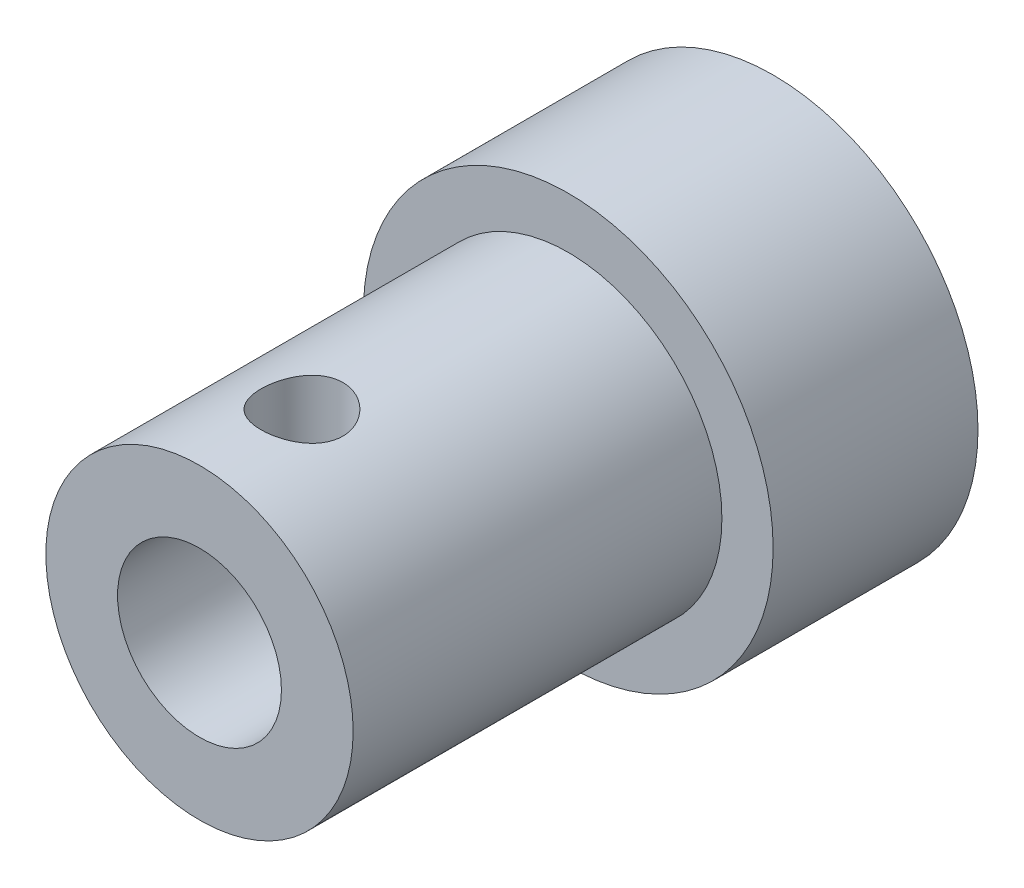
SolidWorks part; units mm, degrees
material "1060 Alloy"
ref_plane "Front Plane" through (0, 0, 0) normal (0, 0, 1) x (1, 0, 0)
ref_plane "Top Plane" through (0, 0, 0) normal (0, 1, 0) x (1, 0, 0)
ref_plane "Right Plane" through (0, 0, 0) normal (1, 0, 0) x (0, 0, -1)
sketch "Sketch1" plane through (0, 0, 0) normal (0, 0, 1) x (1, 0, 0)
  circle A0 centre (0, 0) radius 4
  circle A1 centre (0, 0) radius 7.5
  dimension "D1" = 8
  dimension "D2" = 15
extrude "Boss-Extrude1" add sketch "Sketch1" against normal blind 5 contours A0 | A1 A0
ref_plane "Plane1" through (0, 7.5, 0) normal (0, 1, 0) x (1, 0, 0)
sketch "Sketch3" plane through (0, 0, -5) normal (0, 0, -1) x (-1, 0, 0)
  line L0 (0, 0) -> (0, 7) construction
  line L1 (0, 0) -> (7, 0) construction
  circle A0 centre (0, 0) radius 10
  circle A1 centre (0, 7) radius 1.5
  circle A2 centre (7, 0) radius 1.5
  circle A3 centre (0, -7) radius 1.5
  circle A4 centre (-7, 0) radius 1.5
  dimension "D1" = 20
  dimension "D2" = 3
  dimension "D3" = 7
  dimension "D5" = 90
  dimension "D6" = 7
  dimension "D4" = 4
extrude "Boss-Extrude3" add sketch "Sketch3" along normal blind 8
sketch "Sketch4" plane through (0, 0, 0) normal (0, 0, 1) x (1, 0, 0)
  circle A0 centre (0, 0) radius 4
  circle A1 centre (0, 0) radius 7.5
  circle A2 centre (0, 0) radius 7.5
  dimension "D2" = 8
  dimension "D1" = 0
extrude "Boss-Extrude4" add sketch "Sketch4" along normal blind 15
sketch "Sketch2" plane through (0, 7.5, 0) normal (0, 1, 0) x (1, 0, 0)
  circle A0 centre (0, -10) radius 2
  dimension "D2" = 4
  dimension "D1" = 10
extrude "Cut-Extrude1" cut sketch "Sketch2" against normal blind 7
sketch "Sketch6" plane through (0, 0, 15) normal (0, 0, 1) x (1, 0, 0)
  circle A0 centre (0, 0) radius 4 construction
  circle A1 centre (0, 0) radius 4
extrude "Cut-Extrude2" cut sketch "Sketch6" against normal through all
sketch "Sketch7" plane through (0, 0, -5) normal (0, 0, 1) x (1, 0, 0)
  circle A0 centre (0, 0) radius 10 construction
  circle A1 centre (0, 0) radius 10
  circle A2 centre (0, 0) radius 4 construction
  circle A3 centre (0, 0) radius 4
extrude "Boss-Extrude5" add sketch "Sketch7" along normal blind 2
